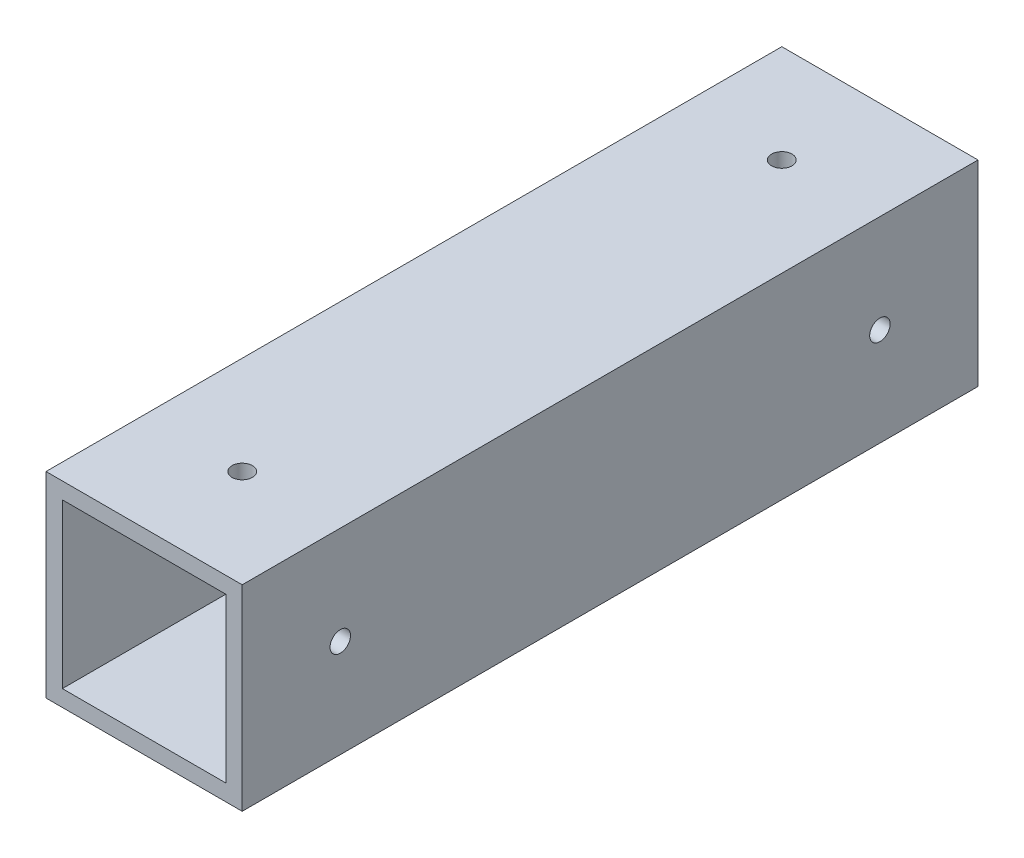
SolidWorks part; units mm, degrees
ref_plane "前视基准面" through (0, 0, 0) normal (0, 0, 1) x (1, 0, 0)
ref_plane "上视基准面" through (0, 0, 0) normal (0, 1, 0) x (1, 0, 0)
ref_plane "右视基准面" through (0, 0, 0) normal (1, 0, 0) x (0, 0, -1)
sketch "草图1" plane through (0, 0, 0) normal (0, 0, 1) x (1, 0, 0)
  line L0 (-12, 12) -> (12, 12)
  line L1 (-10, 10) -> (10, 10)
  line L2 (-10, 10) -> (-10, -10)
  line L3 (-10, -10) -> (10, -10)
  line L4 (10, 10) -> (10, -10)
  line L5 (-10, 10) -> (10, -10) construction
  line L6 (-10, -10) -> (10, 10) construction
  line L7 (12, 12) -> (12, -12)
  line L8 (-12, -12) -> (12, -12)
  line L9 (-12, 12) -> (-12, -12)
  point P0 (0, 0)
  dimension "D1" = 20
  dimension "D2" = 20
  dimension "D3" = 2
extrude "凸台-拉伸1" add sketch "草图1" along normal mid plane 90.01
sketch "草图2" plane through (-12, 0, 0) normal (-1, 0, 0) x (0, 0, 1)
  line L0 (-45.005, 12) -> (-45.005, -12) construction
  circle A0 centre (-33.005, 0) radius 1 construction
  dimension "D1" = 12
hole_wizard "M3 螺纹孔的螺纹孔钻头1" positions "3D草图2" profile "草图3" hole size "M3" standard "GB" end condition through all
sketch3d "3D草图2"
  point P0 (-12, 0, -33.005)
sketch "草图3" plane through (-12, 0, -33.005) normal (0, 1, 0) x (0, 0, 1)
  line L0 (0, 0) -> (0, 24)
  line L1 (0, 24) -> (1.25, 24)
  line L2 (1.25, 24) -> (1.25, 0)
  line L5 (1.25, 0) -> (0, 0)
  line L11 (0, -6.35) -> (0, 107.95) construction
  dimension "通孔孔直径" = 2.5
  dimension "通孔孔深度" = 24
mirror "镜向1" about plane through (0, 0, 0) normal (0, 0, 1) of "M3 螺纹孔的螺纹孔钻头1"
sketch "草图4" plane through (0, 12, 0) normal (0, 1, 0) x (1, 0, 0)
  line L0 (12, 45.005) -> (-12, 45.005) construction
  circle A0 centre (0, 33.005) radius 1 construction
  dimension "D1" = 12
hole_wizard "M3 螺纹孔的螺纹孔钻头2" positions "3D草图3" profile "草图5" hole size "M3" standard "GB" end condition through all
sketch3d "3D草图3"
  point P0 (0, 12, -33.005)
sketch "草图5" plane through (0, 12, -33.005) normal (1, 0, 0) x (0, 0, 1)
  line L0 (0, 0) -> (0, 24)
  line L1 (0, 24) -> (1.25, 24)
  line L2 (1.25, 24) -> (1.25, 0)
  line L5 (1.25, 0) -> (0, 0)
  line L11 (0, -6.35) -> (0, 107.95) construction
  dimension "通孔孔直径" = 2.5
  dimension "通孔孔深度" = 24
mirror "镜向2" about plane through (0, 0, 0) normal (0, 0, 1) of "M3 螺纹孔的螺纹孔钻头2"
